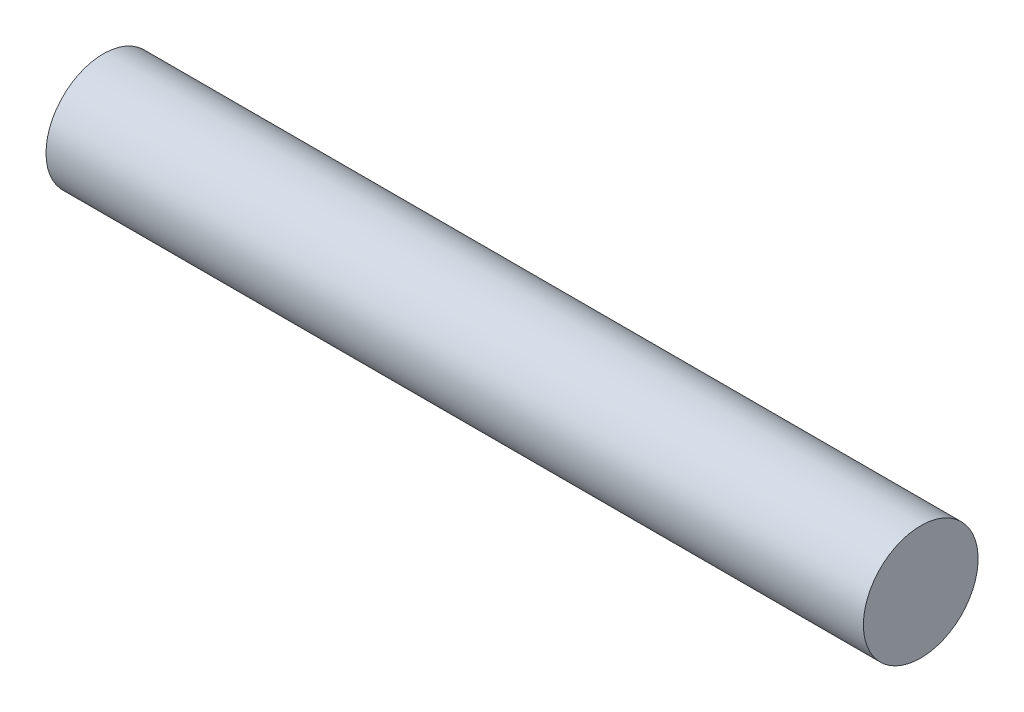
SolidWorks part; units mm, degrees
ref_plane "Front Plane" through (0, 0, 0) normal (0, 0, 1) x (1, 0, 0)
ref_plane "Top Plane" through (0, 0, 0) normal (0, 1, 0) x (1, 0, 0)
ref_plane "Right Plane" through (0, 0, 0) normal (1, 0, 0) x (0, 0, -1)
sketch "Sketch1" plane through (0, 0, 0) normal (0, 0, 1) x (1, 0, 0)
  line L0 (-38.9012, 0) -> (38.9012, 0) construction
  line L1 (0, -13.1461) -> (0, 13.1461) construction
  line L2 (-28.5, 0) -> (28.5, 0)
  line L4 (-28.5, 0) -> (-28.5, 4)
  line L5 (-28.5, 4) -> (28.5, 4)
  line L6 (28.5, 0) -> (28.5, 4)
  point P5 (0, 0)
  dimension "D1" = 57
  dimension "D2" = 8
revolve "Revolve1" add sketch "Sketch1" angle 360 about L0
